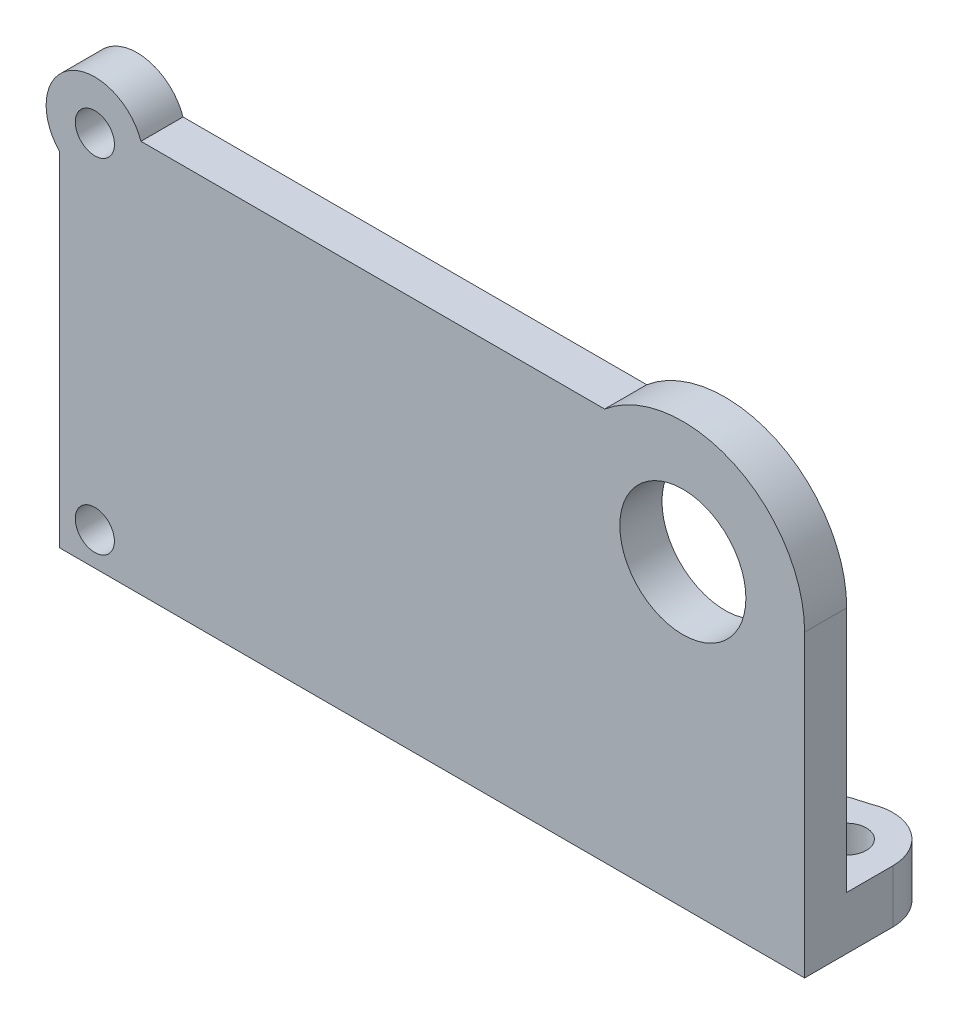
SolidWorks part; units mm, degrees
ref_plane "Front Plane" through (0, 0, 0) normal (0, 0, 1) x (1, 0, 0)
ref_plane "Top Plane" through (0, 0, 0) normal (0, 1, 0) x (1, 0, 0)
ref_plane "Right Plane" through (0, 0, 0) normal (1, 0, 0) x (0, 0, -1)
sketch "Sketch1" plane through (0, 0, 0) normal (0, 0, 1) x (1, 0, 0)
  line L1 (-26.416, -9.8) -> (26.416, -9.8)
  line L2 (-26.416, -9.8) -> (-26.416, 9.8)
  line L3 (-26.416, 9.8) -> (26.416, 9.8)
  line L4 (26.416, -9.8) -> (26.416, 9.8)
  line L5 (-26.416, -9.8) -> (26.416, 9.8) construction
  line L6 (-26.416, 9.8) -> (26.416, -9.8) construction
  line L7 (-20.15, -9.8) -> (20.15, -9.8)
  line L8 (-20.15, -9.8) -> (-20.15, 9.8)
  line L9 (-20.15, 9.8) -> (20.15, 9.8)
  line L10 (20.15, -9.8) -> (20.15, 9.8)
  line L11 (-20.15, -9.8) -> (20.15, 9.8) construction
  line L12 (-20.15, 9.8) -> (20.15, -9.8) construction
  line L13 (-26.416, 9.8) -> (26.416, 9.8)
  line L14 (-26.416, 9.8) -> (-26.416, 14.8)
  line L15 (-26.416, 14.8) -> (26.416, 14.8)
  line L16 (26.416, 9.8) -> (26.416, 14.8)
  line L17 (26.416, -9.8) -> (-26.416, -9.8)
  line L18 (26.416, -9.8) -> (26.416, -14.8)
  line L19 (26.416, -14.8) -> (-26.416, -14.8)
  line L20 (-26.416, -9.8) -> (-26.416, -14.8)
  circle A0 centre (-23.95, -4.974) radius 1.675
  circle A1 centre (-23.95, 4.974) radius 1.675
  circle A2 centre (23.95, 4.974) radius 1.675
  circle A3 centre (23.95, -4.974) radius 1.675
  point P0 (0, 0)
  point P14 (0, 0)
  dimension "D1" = 3.35
  dimension "D2" = 3.35
  dimension "D3" = 3.35
  dimension "D4" = 3.35
  dimension "D7" = 4.826
  dimension "D8" = 3.8
  dimension "D9" = 3.8
  dimension "D10" = 4.826
  dimension "D11" = 4.826
  dimension "D12" = 4.826
  dimension "D13" = 3.8
  dimension "D5" = 19.6
  dimension "D6" = 52.832
  dimension "D15" = 40.3
  dimension "D16" = 5
  dimension "D17" = 5
  dimension "3.9" = 3.8
extrude "Boss-Extrude2" add sketch "Sketch1" along normal blind 3.175 contours L1 L8 L3 L2 A1 A0 | L1 L20 L19 L18 | L3 L16 L15 L14 | L10 L1 L4 L3 A3 A2
sketch "Sketch3" plane through (0, 0, 3.175) normal (0, 0, 1) x (1, 0, 0)
  line L0 (26.416, -14.8) -> (56.416, -14.8)
  line L6 (26.416, 14.8) -> (56.416, 14.8)
  line L7 (26.416, 14.8) -> (26.416, -14.906)
  line L8 (26.416, -14.906) -> (56.416, -14.906)
  line L9 (56.416, 14.8) -> (56.416, -14.906)
  line M3 (26.416, -14.8) -> (26.416, 14.8)
  dimension "D2" = 30
extrude "Boss-Extrude3" add sketch "Sketch3" against normal up to surface (3.175 mm away) contours L9 L6 L0 M3 up to face at (0, 0, 0)
sketch "Sketch4" plane through (0, 0, 0) normal (0, 0, -1) x (-1, 0, 0)
  line L3 (-56.416, 14.8) -> (-56.416, -14.8) construction
  line L4 (-56.416, -14.8) -> (26.416, -14.8) construction
  circle A0 centre (-40.576, 7.77) radius 4.75
  dimension "D1" = 15.84
  dimension "D2" = 22.57
  dimension "D3" = 9.5
extrude "Cut-Extrude1" cut sketch "Sketch4" against normal blind 10 contours A0
sketch "Sketch22" plane through (0, 0, 0) normal (0, 0, -1) x (-1, 0, 0)
  line L0 (-52.3294, 14.8) -> (-30.0917, 14.8)
  line L1 (26.416, 14.8) -> (-56.416, 14.8) construction
  circle A0 centre (-40.576, 7.77) radius 9.175
  dimension "D1" = 18.35
extrude "Boss-Extrude14" add sketch "Sketch22" against normal up to surface (3.175 mm away) contours L0 A0
sketch "Sketch23" plane through (0, 0, 0) normal (0, 0, -1) x (-1, 0, 0)
  line L0 (-49.751, 7.77) -> (-49.751, -14.8)
  line L1 (-56.416, -14.8) -> (26.416, -14.8) construction
  circle A0 centre (-40.576, 7.77) radius 9.175
  line M4 (-46.4717, 14.8) -> (-56.416, 14.8)
  line M5 (-56.416, 14.8) -> (-56.416, -14.8)
  line M6 (-56.416, -14.8) -> (26.416, -14.8)
extrude "Cut-Extrude8" cut sketch "Sketch23" against normal blind 10 contours A0 L0 M4 M5 M6
sketch "Sketch24" plane through (0, 0, 0) normal (0, 0, -1) x (-1, 0, 0)
  line L1 (26.416, 14.8) -> (-34.6803, 14.8) construction
  line L2 (26.416, -14.8) -> (26.416, 14.8) construction
  circle A0 centre (23.736, 13.59) radius 1.675
  dimension "D1" = 3.35
  dimension "D2" = 1.21
  dimension "D3" = 2.68
extrude "Cut-Extrude9" cut sketch "Sketch24" against normal blind 10
sketch "Sketch25" plane through (0, 0, 0) normal (0, 0, -1) x (-1, 0, 0)
  circle A0 centre (23.736, 13.59) radius 1.675
  circle A1 centre (23.95, 4.974) radius 1.675
  circle A2 centre (23.95, -4.974) radius 1.675
  circle A7 centre (23.95, -4.974) radius 3.675
  circle A8 centre (23.95, 4.974) radius 3.675
  circle A9 centre (23.736, 13.59) radius 3.675
  dimension "D1" = 2
  dimension "D2" = 2
extrude "Boss-Extrude15" add sketch "Sketch25" against normal up to surface (3.175 mm away) up to face at (5.1596, 5.6121, 3.175)
sketch "Sketch27" plane through (0, 0, 0) normal (0, 0, -1) x (-1, 0, 0)
  line L1 (-26.8834, 11.0214) -> (26.0491, 11.0214)
  line L2 (-26.8834, 11.0214) -> (-26.8834, -11.9842)
  line L3 (-26.8834, -11.9842) -> (26.0491, -11.9842)
  line L4 (26.0491, 11.0214) -> (26.0491, -11.9842)
extrude "Boss-Extrude16" add sketch "Sketch27" against normal up to surface (3.175 mm away) up to face at (-4.7057, 2.7441, 3.175)
sketch "Sketch28" plane through (0, 0, 0) normal (0, 0, -1) x (-1, 0, 0)
  line L0 (26.416, 8.9779) -> (26.416, -8.886)
  line L1 (26.416, 7.6988) -> (26.416, 11.0754) construction
  line L2 (26.416, -14.8) -> (26.416, -7.6988) construction
  line L3 (26.416, -8.886) -> (33.6957, -3.4148)
  line L4 (33.6957, -3.4148) -> (26.416, 8.9779)
extrude "Cut-Extrude14" cut sketch "Sketch28" against normal blind 10
sketch "Sketch29" plane through (0, 0, 0) normal (0, 0, -1) x (-1, 0, 0)
  line L1 (26.416, -14.8) -> (6.416, -14.8)
  line L2 (26.416, -14.8) -> (26.416, 20.9862)
  line L3 (26.416, 20.9862) -> (6.416, 20.9862)
  line L4 (6.416, -14.8) -> (6.416, 20.9862)
  line L5 (26.416, 20.9862) -> (29.8494, 20.9862)
  line L6 (26.416, 20.9862) -> (26.416, 8.7593)
  line L7 (26.416, 8.7593) -> (29.8494, 8.7593)
  line L8 (29.8494, 20.9862) -> (29.8494, 8.7593)
  line M3 (26.416, -14.8) -> (26.416, 11.0754)
  arc M4 (26.416, 11.0754) -> (20.2659, 14.8) centre (23.736, 13.59) ccw
  line M5 (20.2659, 14.8) -> (-34.6803, 14.8)
  line M8 (-49.751, -14.8) -> (26.416, -14.8)
  circle M10 centre (23.736, 13.59) radius 1.675
  dimension "D1" = 20
extrude "Cut-Extrude15" cut sketch "Sketch29" against normal blind 10 contours L4 L2 M8 M3 M4 M5 M10 | L8 L5 L2 L7 M4 | L2 M4 | L4 L2 L3 M5 M4
sketch "Sketch30" plane through (0, 0, 0) normal (0, 0, -1) x (-1, 0, 0)
  line L0 (6.416, -14.8) -> (6.416, 14.8) construction
  line L1 (6.416, 14.8) -> (-34.6803, 14.8) construction
  circle A0 centre (3.736, 13.59) radius 1.475
  dimension "D1" = 2.95
  dimension "D2" = 2.68
  dimension "D3" = 1.21
extrude "Cut-Extrude16" cut sketch "Sketch30" against normal blind 10
sketch "Sketch31" plane through (0, 0, 0) normal (0, 0, -1) x (-1, 0, 0)
  circle A0 centre (3.736, 13.59) radius 1.675
  circle A1 centre (3.736, 13.59) radius 3.675
  dimension "D1" = 2
extrude "Boss-Extrude17" add sketch "Sketch31" against normal up to surface (3.175 mm away) contours A1 | A0 up to face at (16.5882, 5.6407, 3.175)
sketch "Sketch33" plane through (0, 0, 0) normal (0, 0, -1) x (-1, 0, 0)
  line L0 (-49.751, -14.8) -> (6.416, -14.8) construction
  line L1 (6.416, -14.8) -> (6.416, 11.0754) construction
  circle A0 centre (3.741, -12.3) radius 1.475
  dimension "D1" = 2.95
  dimension "D2" = 2.5
  dimension "D3" = 2.675
extrude "Cut-Extrude17" cut sketch "Sketch33" against normal through all
sketch "Sketch37" plane through (0, -14.8, 0) normal (0, -1, 0) x (-1, 0, 0)
  line L0 (-49.751, -3.175) -> (-49.751, 0) construction
  line L1 (-49.751, 0) -> (6.416, 0) construction
  line L2 (-49.751, 3.475) -> (-49.751, 0)
  line L3 (-49.751, 0) -> (-42.801, 0)
  line L4 (-42.801, 0) -> (-42.801, 3.475)
  circle A0 centre (-46.276, 3.475) radius 1.475
  circle A1 centre (-46.276, 3.475) radius 3.475
  line M4 (6.416, 0) -> (-49.751, 0)
  dimension "D1" = 2.95
  dimension "D3" = 3.475
  dimension "D4" = 3.475
  dimension "D2" = 2
extrude "Boss-Extrude21" add sketch "Sketch37" against normal blind 4 contours A1 L2 L3 | A1 A0 | A1 L4 M4
sketch "Sketch38" plane through (0, -14.8, 0) normal (0, -1, 0) x (-1, 0, 0)
  line L0 (-35.826, 0) -> (-42.801, 0)
  line L1 (-42.801, 0) -> (-42.801, 3.475)
  line L2 (-42.801, 3.475) -> (-46.276, 6.95)
  arc A0 (-46.276, 6.95) -> (-35.826, 0) centre (-48.543, -7.7899) cw
  arc A1 (-42.801, 3.475) -> (-49.751, 3.475) centre (-46.276, 3.475) ccw construction
extrude "Boss-Extrude22" add sketch "Sketch38" against normal blind 4
sketch "Sketch39" plane through (0, 0, 0) normal (0, 0, -1) x (-1, 0, 0)
  circle A0 centre (3.736, 13.59) radius 1.475
  circle A1 centre (3.736, 13.59) radius 1.675
extrude "Boss-Extrude23" add sketch "Sketch39" against normal up to surface (3.175 mm away) up to face at (-5.216, -12.3, 3.175)
